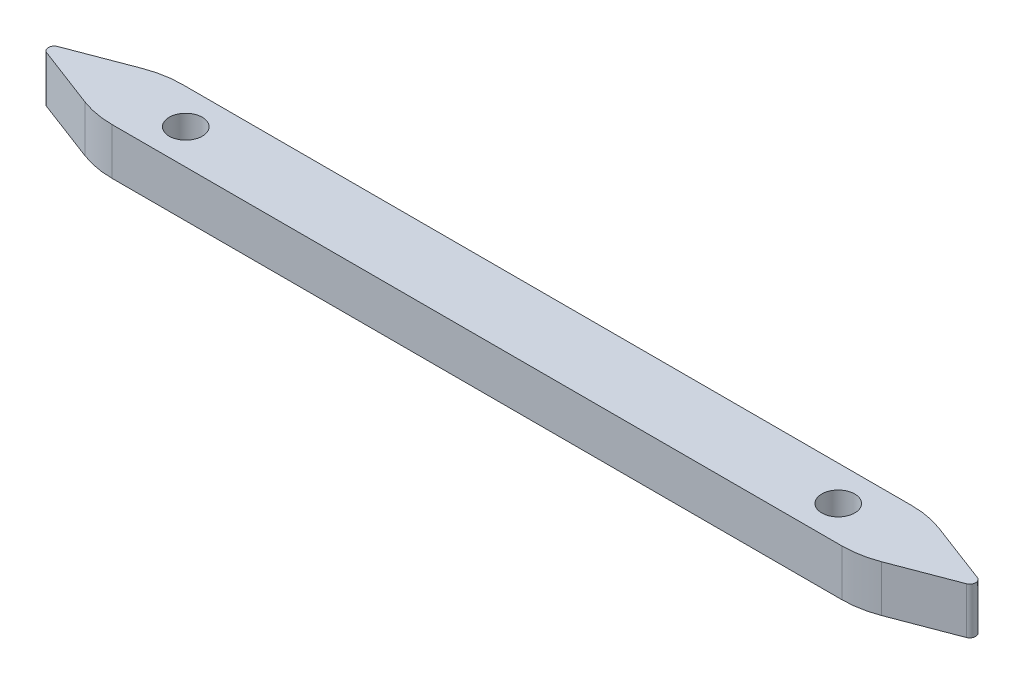
SolidWorks part; units mm, degrees
ref_plane "Front Plane" through (0, 0, 0) normal (0, 0, 1) x (1, 0, 0)
ref_plane "Top Plane" through (0, 0, 0) normal (0, 1, 0) x (1, 0, 0)
ref_plane "Right Plane" through (0, 0, 0) normal (1, 0, 0) x (0, 0, -1)
sketch "Sketch1" plane through (0, 0, 0) normal (0, 1, 0) x (1, 0, 0)
  line L0 (-119.3628, 0) -> (111.8082, 0) construction
  line L1 (0, 90.7812) -> (0, -92.2921) construction
  line L2 (37.205, 9.525) -> (-37.205, 9.525)
  line L3 (-41.7162, 8.6968) -> (-62.6498, 0.742)
  line L4 (37.205, -9.525) -> (-37.205, -9.525)
  line L5 (-41.7162, -8.6968) -> (-62.6498, -0.742)
  line L6 (41.7162, -8.6968) -> (62.6498, -0.742)
  line L7 (41.7162, 8.6968) -> (62.6498, 0.742)
  arc A0 (-37.205, 9.525) -> (-41.7162, 8.6968) centre (-37.205, -3.175) ccw
  arc A1 (-37.205, -9.525) -> (-41.7162, -8.6968) centre (-37.205, 3.175) cw
  arc A2 (-62.6498, -0.742) -> (-62.6498, 0.742) centre (-62.3679, 0) cw
  arc A3 (37.205, -9.525) -> (41.7162, -8.6968) centre (37.205, 3.175) ccw
  arc A4 (62.6498, -0.742) -> (62.6498, 0.742) centre (62.3679, 0) ccw
  arc A5 (37.205, 9.525) -> (41.7162, 8.6968) centre (37.205, -3.175) cw
  point P6 (-64.6024, 0)
  point P18 (0, -9.525)
  point P26 (0, 9.525)
  dimension "D1" = 12.7
  dimension "D2" = 0.7937
  dimension "D3" = 19.05
extrude "Boss-Extrude2" add sketch "Sketch1" along normal blind 22.225 and the other way blind 10
sketch "Sketch2" plane through (0, 0, 9.525) normal (0, 0, 1) x (1, 0, 0)
  line L0 (-37.205, 22.225) -> (37.205, 22.225) construction
  line L1 (-68.6771, 15.875) -> (84.4664, 15.875)
  line L2 (-68.6771, 15.875) -> (-68.6771, 9.525)
  line L3 (-68.6771, 9.525) -> (84.4664, 9.525)
  line L4 (84.4664, 15.875) -> (84.4664, 9.525)
  dimension "D1" = 6.35
  dimension "D2" = 6.35
extrude "Cut-Extrude1" cut sketch "Sketch2" against normal blind 4.7625
sketch "Sketch3" plane through (0, 0, -9.525) normal (0, 0, -1) x (-1, 0, 0)
  line L0 (-37.205, 22.225) -> (37.205, 22.225) construction
  line L1 (-67.7785, 15.875) -> (84.9799, 15.875)
  line L2 (-67.7785, 15.875) -> (-67.7785, 9.525)
  line L3 (-67.7785, 9.525) -> (84.9799, 9.525)
  line L4 (84.9799, 15.875) -> (84.9799, 9.525)
  dimension "D1" = 6.35
  dimension "D2" = 6.35
extrude "Cut-Extrude2" cut sketch "Sketch3" against normal blind 4.7625
fillet "Fillet3" radius 12.7 1 edges at (52.0695, 12.7, -4.7625)
fillet "Fillet4" radius 12.7 1 edges at (52.0695, 12.7, 4.7625)
fillet "Fillet5" radius 12.7 1 edges at (-52.0695, 12.7, 4.7625)
fillet "Fillet6" radius 12.7 1 edges at (-52.0695, 12.7, -4.7625)
sketch "Sketch12" plane through (0, 0, 0) normal (1, 0, 0) x (0, 0, -1)
  circle A0 centre (0, -168.402) radius 168.402
extrude "Cut-Extrude3" cut sketch "Sketch12" against normal blind 84.675 and the other way blind 94.675
sketch "Sketch19" plane through (0, 22.225, 0) normal (0, 1, 0) x (1, 0, 0)
  point P0 (-44.45, 0)
  point P1 (44.45, 0)
hole_wizard "CSK for #8 Flat Head Socket Cap Screw2" positions "Sketch21" profile "Sketch20" countersink size "#8" standard "ANSI Inch" end condition through all
sketch "Sketch21" plane through (0, 22.225, 0) normal (0, 1, 0) x (1, 0, 0)
  point P0 (-44.45, 0)
  point P3 (44.45, 0)
sketch "Sketch20" plane through (-44.45, 22.225, 0) normal (1, 0, 0) x (0, 0, 1)
  line L0 (0, 0) -> (0, 23.3241)
  line L1 (0, 23.3241) -> (2.2479, 23.3241)
  line L2 (2.2479, 23.3241) -> (2.2479, 2.659)
  line L3 (2.2479, 2.659) -> (4.5593, 0)
  line L5 (4.5593, 0) -> (0, 0)
  line L6 (-2.2479, 2.659) -> (-4.5593, 0) construction
  line L11 (0, -6.35) -> (0, 107.95) construction
  dimension "Thru Hole Dia." = 4.4958
  dimension "Thru Hole Depth" = 23.3241
  dimension "Near C'Sink Dia." = 9.1186
  dimension "Near C'Sink Angle" = 82
ref_plane "Plane6" through (0, 3.175, 0) normal (0, 1, 0) x (1, 0, 0)
ref_plane "Plane7" through (0, 9.525, 0) normal (0, 1, 0) x (1, 0, 0)
ref_plane "Plane8" through (0, 15.875, 0) normal (0, 1, 0) x (1, 0, 0)
sketch "Sketch25" plane through (0, 15.875, 0) normal (0, 1, 0) x (1, 0, 0)
  line L1 (-73.1384, 16.8069) -> (78.6977, 16.8069)
  line L2 (-73.1384, 16.8069) -> (-73.1384, -29.4927)
  line L3 (-73.1384, -29.4927) -> (78.6977, -29.4927)
  line L4 (78.6977, 16.8069) -> (78.6977, -29.4927)
extrude "Cut-Extrude4" cut sketch "Sketch25" along normal blind 10.16
sketch "Sketch26" plane through (0, 9.525, 0) normal (0, 1, 0) x (1, 0, 0)
  line L1 (-69.1745, 13.0007) -> (69.3401, 13.0007)
  line L2 (-69.1745, 13.0007) -> (-69.1745, -14.8445)
  line L3 (-69.1745, -14.8445) -> (69.3401, -14.8445)
  line L4 (69.3401, 13.0007) -> (69.3401, -14.8445)
extrude "Cut-Extrude5" cut sketch "Sketch26" against normal blind 23.368
